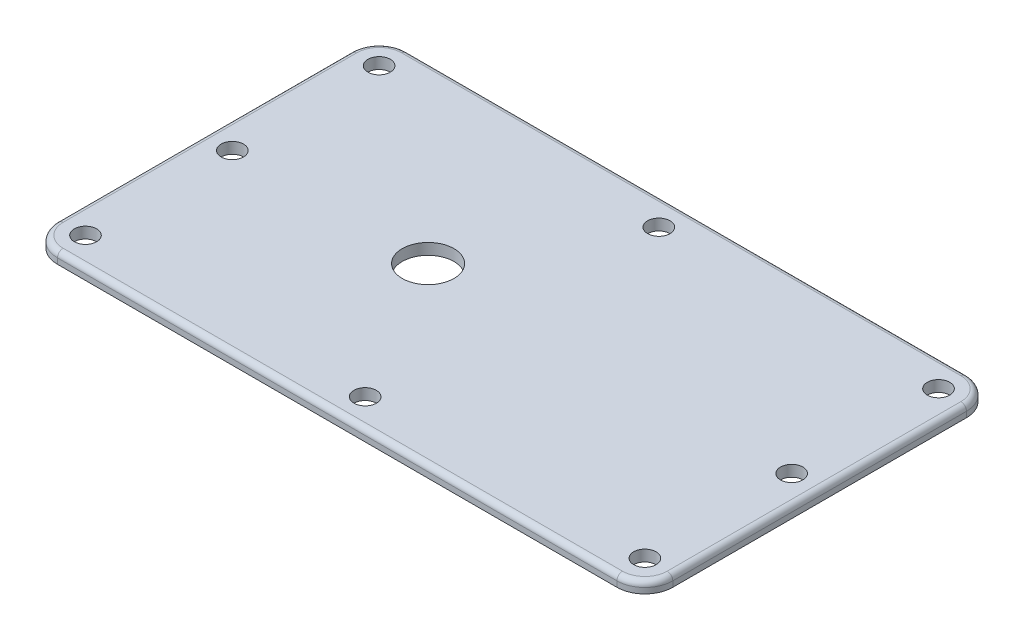
SolidWorks part; units mm, degrees
ref_plane "Front" through (0, 0, 0) normal (0, 0, 1) x (1, 0, 0)
ref_plane "Top" through (0, 0, 0) normal (0, 1, 0) x (1, 0, 0)
ref_plane "Right" through (0, 0, 0) normal (1, 0, 0) x (0, 0, -1)
sketch "Sketch1" plane through (0, 0, 0) normal (0, 1, 0) x (1, 0, 0)
  line L0 (-90.5714, 63.8393) -> (109.4286, 63.8393)
  line L1 (119.4286, 53.8393) -> (119.4286, -51.1607)
  line L2 (109.4286, -61.1607) -> (-90.5714, -61.1607)
  line L3 (-100.5714, -51.1607) -> (-100.5714, 53.8393)
  arc A0 (109.4286, 63.8393) -> (119.4286, 53.8393) centre (109.4286, 53.8393) cw
  arc A1 (119.4286, -51.1607) -> (109.4286, -61.1607) centre (109.4286, -51.1607) cw
  arc A2 (-90.5714, -61.1607) -> (-100.5714, -51.1607) centre (-90.5714, -51.1607) cw
  arc A3 (-90.5714, 63.8393) -> (-100.5714, 53.8393) centre (-90.5714, 53.8393) ccw
  point P6 (119.4286, 63.8393)
  point P9 (119.4286, -61.1607)
  point P14 (-100.5714, 63.8393)
  dimension "D3" = 10
  dimension "D1" = 220
  dimension "D2" = 125
extrude "Boss-Extrude1" add sketch "Sketch1" along normal blind 4
fillet "Fillet1" radius 2 8 edges at (-97.6425, 4, 58.2318) (-100.5714, 4, -1.3393) (-97.6425, 4, -60.9104) (9.4286, 4, -63.8393) (116.4996, 4, -60.9104) (119.4286, 4, -1.3393) (116.4996, 4, 58.2318) (9.4286, 4, 61.1607)
sketch "Sketch2" plane through (0, 4, 0) normal (0, 1, 0) x (1, 0, 0)
  line L0 (-90.5714, 53.8393) -> (109.4286, 53.8393)
  line L1 (109.4286, 53.8393) -> (109.4286, -51.1607)
  line L2 (109.4286, -51.1607) -> (-90.5714, -51.1607)
  line L3 (-90.5714, -51.1607) -> (-90.5714, 53.8393)
  line L4 (-90.5714, 1.3393) -> (109.4286, 1.3393)
  line L5 (9.4286, -51.1607) -> (9.4286, 53.8393)
hole_wizard "Ø8.0mm Dowel Hole1" positions "Sketch8" profile "Sketch9" hole size "Ø8.0" standard "ISO" end condition through all
sketch "Sketch8" plane through (0, 4, 0) normal (0, 1, 0) x (1, 0, 0)
  point P0 (-90.5714, 53.8393)
  point P3 (109.4286, 53.8393)
  point P6 (-90.5714, -51.1607)
  point P9 (109.4286, -51.1607)
  point P12 (109.4286, 1.3393)
  point P14 (9.4286, 53.8393)
  point P16 (-90.5714, 1.3393)
  point P18 (9.4286, -51.1607)
sketch "Sketch9" plane through (-90.5714, 4, -53.8393) normal (1, 0, 0) x (0, 0, 1)
  line L0 (0, 0) -> (0, 4)
  line L1 (0, 4) -> (4, 4)
  line L2 (4, 4) -> (4, 0)
  line L5 (4, 0) -> (0, 0)
  line L11 (0, -6.35) -> (0, 107.95) construction
  dimension "Thru Hole Dia." = 8
  dimension "Thru Hole Depth" = 4
sketch "Sketch10" plane through (0, 4, 0) normal (0, 1, 0) x (1, 0, 0)
  line L0 (9.4286, 53.8393) -> (9.4286, -51.1607)
  line L1 (9.4286, 1.3393) -> (-20.5714, 1.3393)
  dimension "D1" = 30
hole_wizard "M20x1.5 Tapped Hole1" positions "Sketch11" profile "Sketch12" tap size "M20x1.5" standard "ISO" end condition through all
sketch "Sketch11" plane through (0, 4, 0) normal (0, 1, 0) x (1, 0, 0)
  point P0 (-20.5714, 1.3393)
sketch "Sketch12" plane through (-20.5714, 4, -1.3393) normal (1, 0, 0) x (0, 0, 1)
  line L0 (0, 0) -> (0, 4)
  line L1 (0, 4) -> (9.25, 4)
  line L2 (9.25, 4) -> (9.25, 0)
  line L5 (9.25, 0) -> (0, 0)
  line L11 (0, -6.35) -> (0, 107.95) construction
  dimension "Thru Tap Drill Dia." = 18.5
  dimension "Thru Tap Drill Depth" = 4
cosmetic thread "Hole Thread1" parameters "D2"=20
